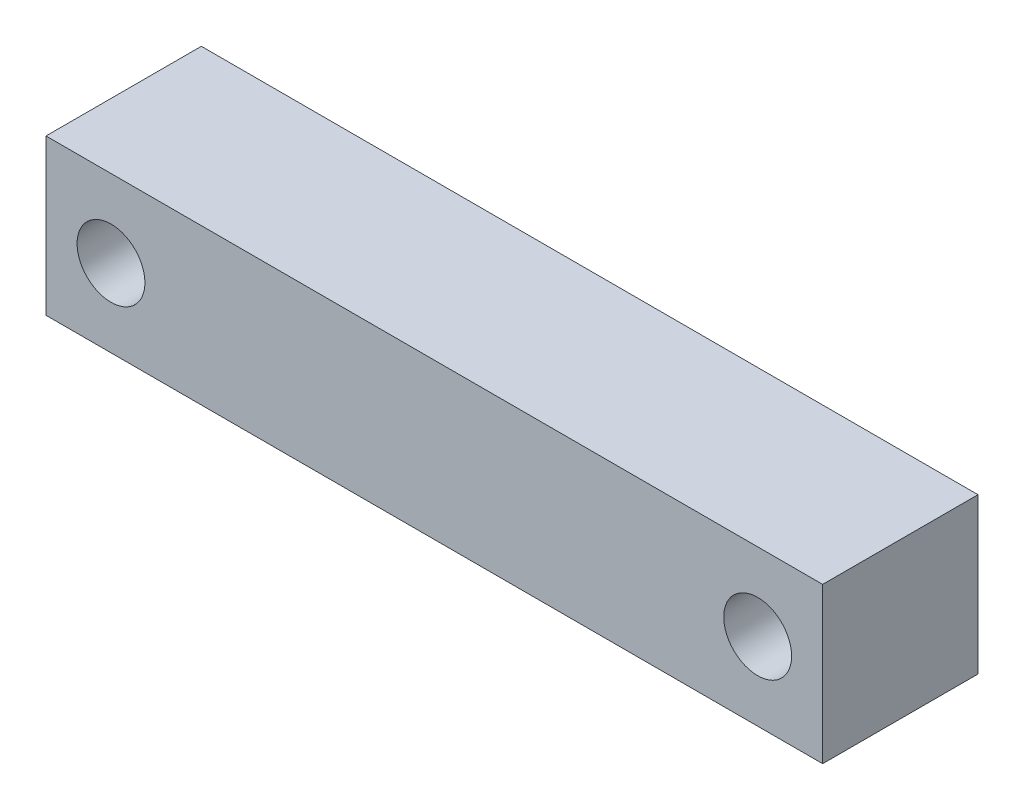
SolidWorks part; units mm, degrees
ref_plane "Front Plane" through (0, 0, 0) normal (0, 0, 1) x (1, 0, 0)
ref_plane "Top Plane" through (0, 0, 0) normal (0, 1, 0) x (1, 0, 0)
ref_plane "Right Plane" through (0, 0, 0) normal (1, 0, 0) x (0, 0, -1)
sketch "Sketch2" plane through (0, 0, 0) normal (0, 0, 1) x (1, 0, 0)
  line L1 (-12.5, -2.5) -> (12.5, -2.5)
  line L2 (-12.5, -2.5) -> (-12.5, 2.5)
  line L3 (-12.5, 2.5) -> (12.5, 2.5)
  line L4 (12.5, -2.5) -> (12.5, 2.5)
  line L5 (-12.5, -2.5) -> (12.5, 2.5) construction
  line L6 (-12.5, 2.5) -> (12.5, -2.5) construction
  point P0 (0, 0)
  dimension "D1" = 25
  dimension "D2" = 5
extrude "Boss-Extrude1" add sketch "Sketch2" along normal blind 5
sketch "Sketch3" plane through (0, 0, 5) normal (0, 0, 1) x (1, 0, 0)
  line L0 (12.5, 2.5) -> (-12.5, 2.5) construction
  line L1 (-12.5, 2.5) -> (-12.5, -2.5) construction
  point P0 (-10.4078, 0)
  point P1 (10.4078, 0)
  dimension "D1" = 2.5
  dimension "D2" = 20.8156
  dimension "D3" = 2.0922
hole_wizard "#44 (0.086) Diameter Hole1" positions "3DSketch1" profile "Sketch4" hole size "#44" standard "ANSI Inch" end condition through all
sketch3d "3DSketch1"
  point P0 (-10.4078, 0, 5)
  point P3 (10.4078, 0, 5)
sketch "Sketch4" plane through (-10.4078, 0, 5) normal (1, 0, 0) x (0, -1, 0)
  line L0 (0, 0) -> (0, 5)
  line L1 (0, 5) -> (1.0922, 5)
  line L2 (1.0922, 5) -> (1.0922, 0)
  line L5 (1.0922, 0) -> (0, 0)
  line L11 (0, -6.35) -> (0, 107.95) construction
  dimension "Thru Hole Dia." = 2.1844
  dimension "Thru Hole Depth" = 5
sketch "Sketch5" plane through (0, 0, 0) normal (0, 0, -1) x (-1, 0, 0)
  line L1 (-11.5, -1.5) -> (12.5, -1.5)
  line L2 (-11.5, -1.5) -> (-11.5, 1.5)
  line L3 (-11.5, 1.5) -> (12.5, 1.5)
  line L4 (12.5, -1.5) -> (12.5, 1.5)
  line L5 (-11.5, -1.5) -> (12.5, 1.5) construction
  line L6 (-11.5, 1.5) -> (12.5, -1.5) construction
  line L7 (-12.5, 2.5) -> (12.5, 2.5) construction
  line L8 (12.5, 2.5) -> (12.5, -2.5) construction
  point P0 (0, 0)
  dimension "D1" = 1
  dimension "D2" = 24
extrude "Cut-Extrude1" cut sketch "Sketch5" against normal blind 3
